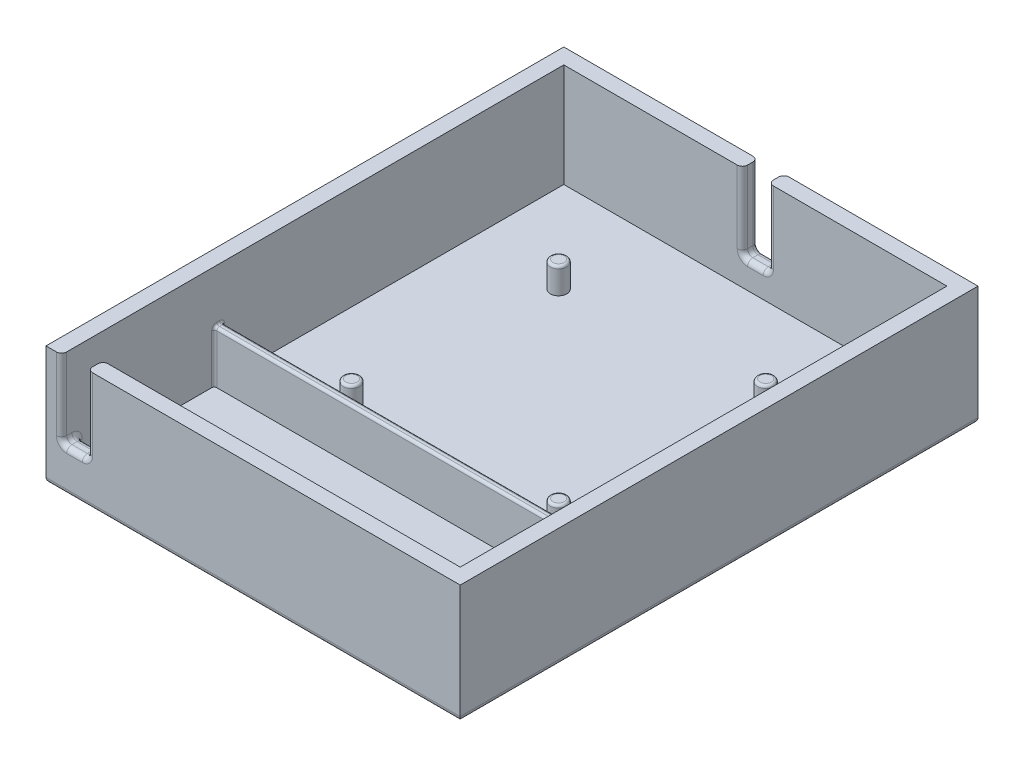
SolidWorks part; units mm, degrees
ref_plane "Front" through (0, 0, 0) normal (0, 0, 1) x (1, 0, 0)
ref_plane "Top" through (0, 0, 0) normal (0, 1, 0) x (1, 0, 0)
ref_plane "Right" through (0, 0, 0) normal (1, 0, 0) x (0, 0, -1)
sketch "Sketch1" plane through (0, 0, 0) normal (0, 1, 0) x (1, 0, 0)
  line L1 (-40, 50) -> (40, 50)
  line L2 (-40, 50) -> (-40, -50)
  line L3 (-40, -50) -> (40, -50)
  line L4 (40, 50) -> (40, -50)
  line L5 (-40, 50) -> (40, -50) construction
  line L6 (-40, -50) -> (40, 50) construction
  point P0 (0, 0)
  dimension "D1" = 80
  dimension "D2" = 100
extrude "Boss-Extrude1" add sketch "Sketch1" along normal blind 3
sketch "Sketch2" plane through (0, 3, 0) normal (0, 1, 0) x (1, 0, 0)
  line L0 (37, 47) -> (-37, 47)
  line L1 (-37, 47) -> (-37, -47)
  line L2 (-37, -47) -> (37, -47)
  line L3 (37, -47) -> (37, 47)
  line L4 (40, -50) -> (40, 50)
  line L5 (40, 50) -> (-40, 50)
  line L6 (-40, 50) -> (-40, -50)
  line L7 (-40, -50) -> (40, -50)
  line L8 (40, -50) -> (40, 50)
  line L9 (40, 50) -> (-40, 50)
  line L10 (-40, 50) -> (-40, -50)
  line L11 (-40, -50) -> (40, -50)
  dimension "D1" = 0
  dimension "D2" = 3
extrude "Boss-Extrude2" add sketch "Sketch2" along normal blind 20
sketch "Sketch3" plane through (0, 3, 0) normal (0, 1, 0) x (1, 0, 0)
  line L0 (-37, 29) -> (37, 29) construction
  line L1 (-37, 47) -> (-37, -47) construction
  line L2 (37, -47) -> (37, 47) construction
  line L3 (-37, -11) -> (37, -11) construction
  line L4 (37, -47) -> (37, 47) construction
  line L5 (37, 47) -> (-37, 47) construction
  line L6 (0, 47) -> (0, -11) construction
  line L7 (37, 47) -> (-37, 47) construction
  circle A0 centre (-20, 29) radius 1.6
  circle A1 centre (-20, -11) radius 1.6
  circle A2 centre (20, -11) radius 1.6
  circle A3 centre (20, 29) radius 1.6
  dimension "D3" = 3.2
  dimension "D4" = 3.2
  dimension "D1" = 40
  dimension "D2" = 18
  dimension "D5" = 40
  dimension "D6" = 40
extrude "Boss-Extrude3" add sketch "Sketch3" along normal blind 5
sketch "Sketch4" plane through (0, 3, 0) normal (0, 1, 0) x (1, 0, 0)
  line L0 (-37, -20.5) -> (37, -20.5) construction
  line L1 (-37, 47) -> (-37, -47) construction
  line L2 (37, -47) -> (37, 47) construction
  line L3 (-37, -47) -> (37, -47) construction
  line L4 (-37, -20.5) -> (37, -20.5)
  line L5 (-37, -19) -> (37, -19)
  line L6 (-37, -20.5) -> (-37, -19)
  line L7 (37, -20.5) -> (37, -19)
  dimension "D1" = 26.5
  dimension "D2" = 1.5
extrude "Boss-Extrude4" add sketch "Sketch4" along normal blind 10
sketch "Sketch6" plane through (0, 23, 0) normal (0, 1, 0) x (1, 0, 0)
  line L0 (0, 50) -> (0, -50) construction
  line L1 (40, 50) -> (-40, 50) construction
  line L2 (-40, -50) -> (40, -50) construction
  line L4 (-37, -47) -> (-32, -47)
  line L5 (-37, -47) -> (-37, -50)
  line L6 (-37, -50) -> (-32, -50)
  line L7 (-32, -47) -> (-32, -50)
  line L8 (-2.5, 44.3225) -> (2.5, 44.3225)
  line L9 (-2.5, 44.3225) -> (-2.5, 52.4929)
  line L10 (-2.5, 52.4929) -> (2.5, 52.4929)
  line L11 (2.5, 44.3225) -> (2.5, 52.4929)
  line L12 (-2.5, 44.3225) -> (2.5, 52.4929) construction
  line L13 (-2.5, 52.4929) -> (2.5, 44.3225) construction
  point P11 (0, 48.4077)
  dimension "D1" = 5
  dimension "D2" = 5
extrude "Cut-Extrude1" cut sketch "Sketch6" against normal blind 15
fillet "Fillet1" radius 1 16 edges at (-32, 15.5, 47) (-37, 5.5, 47) (-32, 15.5, 50) (-37, 15.5, 50) (-2.5, 15.5, -50) (2.5, 15.5, -50) (2.5, 15.5, -47) (-2.5, 15.5, -47) (-34.5, 8, 47) (-32, 8, 48.5) (-34.5, 8, 50) (-37, 8, 48.5) (0, 8, -50) (2.5, 8, -48.5) (0, 8, -47) (-2.5, 8, -48.5)
fillet "Fillet2" radius 0.5 12 edges at (37, 8, 19) (-37, 8, 19) (37, 8, 20.5) (-37, 8, 20.5) (20, 8, -30.6) (-20, 8, -27.4) (-20, 8, 12.6) (20, 8, 9.4) (0, 13, 19) (37, 13, 19.75) (0, 13, 20.5) (-37, 13, 19.75)
fillet "Fillet3" radius 1 4 edges at (0, 0, -50) (-40, 0, 0) (0, 0, 50) (40, 0, 0)
